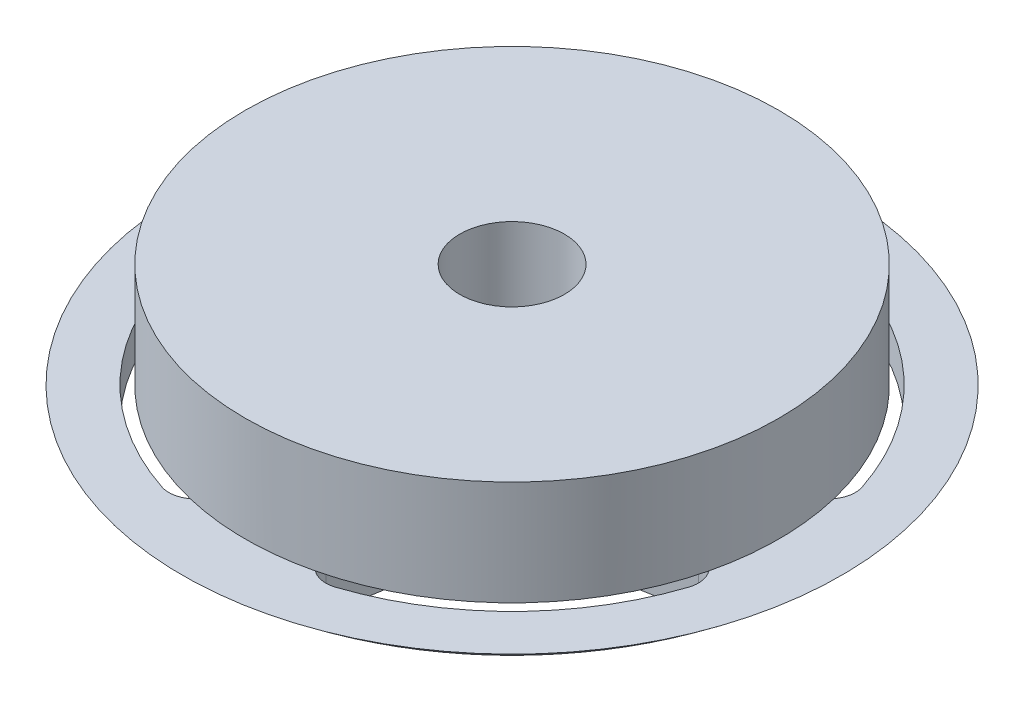
SolidWorks part; units mm, degrees
ref_plane "Front Plane" through (0, 0, 0) normal (0, 0, 1) x (1, 0, 0)
ref_plane "Top Plane" through (0, 0, 0) normal (0, 1, 0) x (1, 0, 0)
ref_plane "Right Plane" through (0, 0, 0) normal (1, 0, 0) x (0, 0, -1)
sketch "Sketch1" plane through (0, 0, 0) normal (0, 0, 1) x (1, 0, 0)
  line L0 (0, 0) -> (0, 22) construction
  line L1 (0, 11) -> (-31.5, 11) construction
  line L2 (-2.5, 2) -> (-2.5, 0)
  line L3 (-2.5, 0) -> (-15, 0)
  line L4 (-2.5, 2) -> (-5, 4.5)
  line L5 (-5, 4.5) -> (-5, 16)
  line L6 (-5, 16) -> (-25.5, 16)
  line L7 (-25.5, 16) -> (-25.5, 6)
  line L8 (-25.5, 6) -> (-31.5, 6)
  arc A0 (-15, 0) -> (-31.5, 6) centre (-15, 25.6875) cw
  point P7 (-25.5, 11)
  dimension "D1" = 22
  dimension "D2" = 63
  dimension "D3" = 30
  dimension "D4" = 5
  dimension "D5" = 10
  dimension "D6" = 2
  dimension "D7" = 45
  dimension "D8" = 10
  dimension "D9" = 6
revolve "Revolve1" add sketch "Sketch1" angle 360 about L0
hole_wizard "M3x0.5 Tapped Hole1" positions "Sketch3" profile "Sketch2" tap size "M3x0.5" standard "ANSI Metric"
sketch "Sketch3" plane through (0, 0, 0) normal (0, -1, 0) x (-1, 0, 0)
  line L0 (0, 12.5) -> (0, -12.5) construction
  line L3 (-12.5, 0) -> (12.5, 0) construction
  point P0 (12.5, 0)
  point P2 (-12.5, 0)
  point P4 (0, 12.5)
  point P6 (0, -12.5)
  dimension "D1" = 25
sketch "Sketch2" plane through (-12.5, 0, 0) normal (1, 0, 0) x (0, 0, -1)
  line L0 (0, 0) -> (0, 8.2511)
  line L1 (0, 8.2511) -> (1.25, 7.5)
  line L2 (1.25, 7.5) -> (1.25, 0)
  line L5 (1.25, 0) -> (0, 0)
  line L10 (0, 8.2511) -> (-1.25, 7.5) construction
  line L11 (0, -6.35) -> (0, 107.95) construction
  dimension "Tap Drill Dia." = 2.5
  dimension "Tap Drill Depth" = 7.5
  dimension "Drill Angle" = 118
sketch "Sketch4" plane through (0, 0, 0) normal (0, -1, 0) x (1, 0, 0)
  line L0 (0, 0) -> (0, -31.5) construction
  line L1 (0, 0) -> (-31.5, 0) construction
  line L2 (-5, -15.8114) -> (-5, -22.798)
  line L3 (-15.8114, -5) -> (-22.798, -5)
  line L4 (-5, -19.3047) -> (0, -19.3047) construction
  line L5 (-19.3047, -5) -> (-19.3047, 0) construction
  circle A0 centre (0, 0) radius 31.5 construction
  arc A1 (-6.4286, -13.5526) -> (-13.5526, -6.4286) centre (0, 0) cw
  circle A2 centre (0, 0) radius 15 construction
  arc A3 (-8.2812, -25.1728) -> (-25.1728, -8.2812) centre (0, 0) cw
  arc A4 (-25.1728, -8.2812) -> (-22.798, -5) centre (-22.798, -7.5) cw
  arc A5 (-13.5526, -6.4286) -> (-15.8114, -5) centre (-15.8114, -7.5) ccw
  arc A6 (-5, -22.798) -> (-8.2812, -25.1728) centre (-7.5, -22.798) cw
  arc A7 (-6.4286, -13.5526) -> (-5, -15.8114) centre (-7.5, -15.8114) cw
  point P24 (-5, -14.1421)
  dimension "D2" = 5
  dimension "D3" = 2.5
  dimension "D1" = 10
extrude "Cut-Extrude1" cut sketch "Sketch4" against normal up to surface (6 mm away) up to face at (0, 6, -31.5)
pattern_circular "CirPattern1" count 4 over 360 about axis through (0, 0, 0) along (0, 1, 0) of "Cut-Extrude1"
